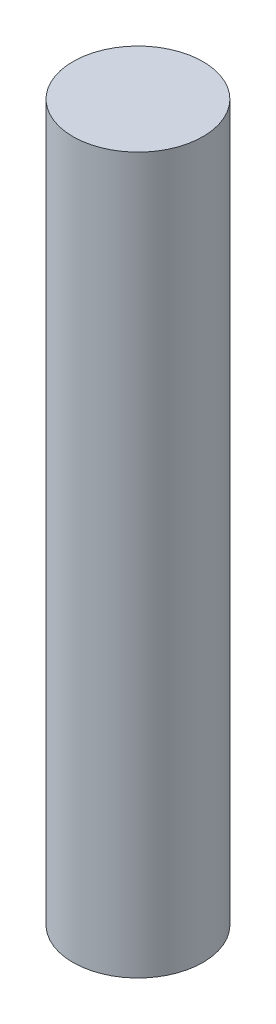
SolidWorks part; units mm, degrees
ref_plane "Front Plane" through (0, 0, 0) normal (0, 0, 1) x (1, 0, 0)
ref_plane "Top Plane" through (0, 0, 0) normal (0, 1, 0) x (1, 0, 0)
ref_plane "Right Plane" through (0, 0, 0) normal (1, 0, 0) x (0, 0, -1)
sketch "Sketch1" plane through (0, 0, 0) normal (0, 1, 0) x (1, 0, 0)
  circle A0 centre (0, 0) radius 2
extrude "Boss-Extrude1" add sketch "Sketch1" along normal blind 9 and the other way blind 13
